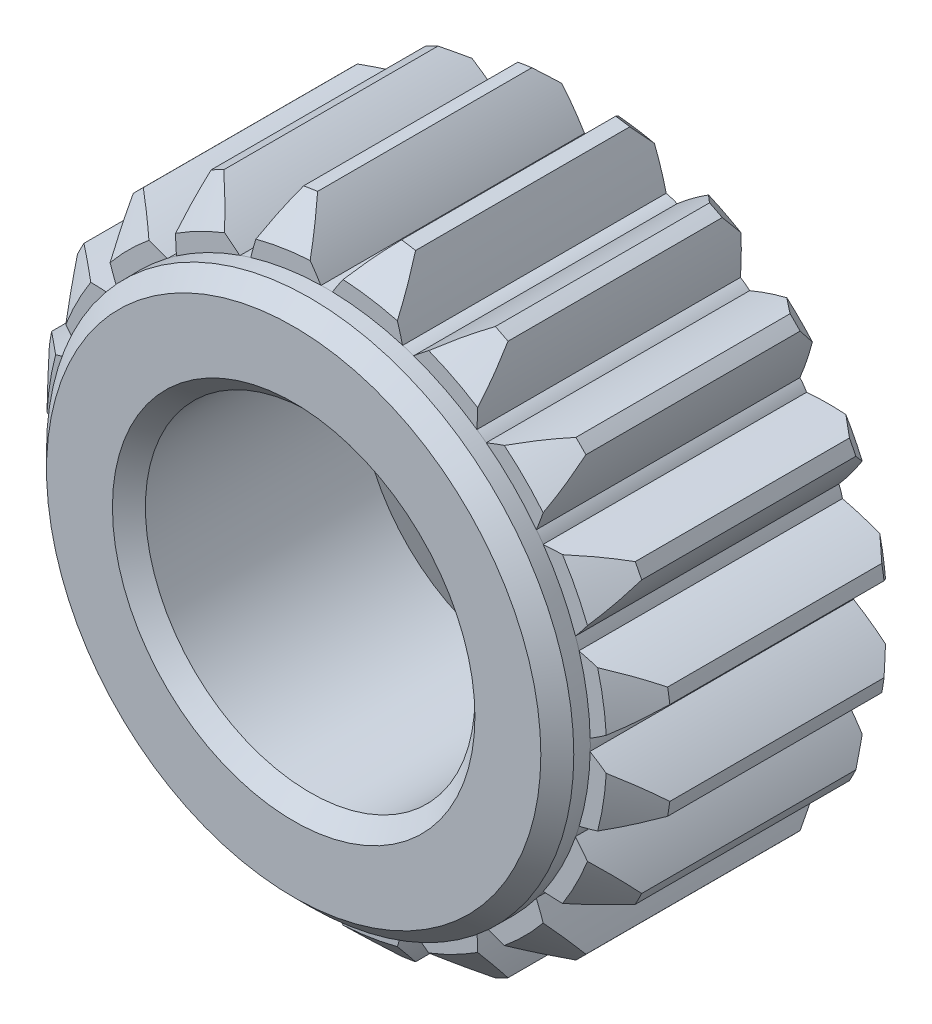
SolidWorks part; units mm, degrees
ref_plane "Front Plane" through (0, 0, 0) normal (0, 0, 1) x (1, 0, 0)
ref_plane "Top Plane" through (0, 0, 0) normal (0, 1, 0) x (1, 0, 0)
ref_plane "Right Plane" through (0, 0, 0) normal (1, 0, 0) x (0, 0, -1)
sketch "Sketch1" plane through (0, 0, 0) normal (0, 0, 1) x (1, 0, 0)
  circle A0 centre (0, 0) radius 9.5
  dimension "D1" = 19
extrude "Boss-Extrude1" add sketch "Sketch1" along normal mid plane 8
chamfer "Front Chamfer" distance 1 angle 45 1 edges at (9.5, 0, 4)
chamfer "Rear Chamfer" distance 0.5 angle 45 1 edges at (9.5, 0, -4)
sketch "Sketch2" plane through (0, 0, 4) normal (0, 0, 1) x (1, 0, 0)
  line L3 (-11.4306, 0) -> (12.9819, 0) construction
  line L4 (0, 0) -> (0, 9.5) construction
  line L5 (0, 0) -> (1.2729, 9.4143) construction
  line L6 (0, 0) -> (-1.2729, 9.4143) construction
  line L7 (0, 0) -> (0.1854, 8.498) construction
  line L8 (0, 0) -> (-0.1854, 8.498) construction
  arc A0 (-1.2729, 9.4143) -> (1.2729, 9.4143) centre (0, 0) cw
  circle A4 centre (0, 0) radius 9.5 construction
  circle A5 centre (0, 0) radius 8.5 construction
  arc A6 (-1.2729, 9.4143) -> (-0.1743, 7.9898) centre (-7.0185, 3.8477) cw
  arc A7 (1.2729, 9.4143) -> (0.1743, 7.9898) centre (7.0185, 3.8477) ccw
  arc A8 (-0.1743, 7.9898) -> (0.1743, 7.9898) centre (0, 6.5) cw
  point P22 (0, 8)
  dimension "D1" = 7.7
  dimension "D2" = 15.4
  dimension "D4" = 8
  dimension "D5" = 3
  dimension "D6" = 1.5
  dimension "D7" = 8.004
  dimension "D9" = 2.5
  dimension "D3" = 7.7
  dimension "D8" = 2.5457
extrude "Cut-Extrude1" cut sketch "Sketch2" against normal through all
pattern_circular "CirPattern1" count 20 over 360 about axis through (0, 0, 0) along (0, 0, 1) of "Cut-Extrude1"
sketch "Sketch3" plane through (0, 0, 4) normal (0, 0, 1) x (1, 0, 0)
  circle A72 centre (0, 0) radius 8
  arc A75 (4.5553, -6.5664) -> (4.8373, -6.3614) centre (3.8206, -5.2586) ccw construction
extrude "Boss-Extrude2" add sketch "Sketch3" along normal blind 1
chamfer "Chamfer3" distance 0.5 angle 45 1 edges at (8, 0, 5)
sketch "Sketch4" plane through (0, 0, 5) normal (0, 0, 1) x (1, 0, 0)
  circle A0 centre (0, 0) radius 5
  dimension "D1" = 10
extrude "Cut-Extrude2" cut sketch "Sketch4" against normal blind 5
sketch "Sketch5" plane through (0, 0, 0) normal (0, 0, 1) x (1, 0, 0)
  circle A0 centre (0, 0) radius 5
  dimension "D1" = 10
extrude "Cut-Extrude3" cut sketch "Sketch5" against normal through all
chamfer "Chamfer4" distance 0.5 angle 45 1 edges at (5, 0, 5)
chamfer "Chamfer5" distance 2 angle 45 1 edges at (5, 0, -4)
